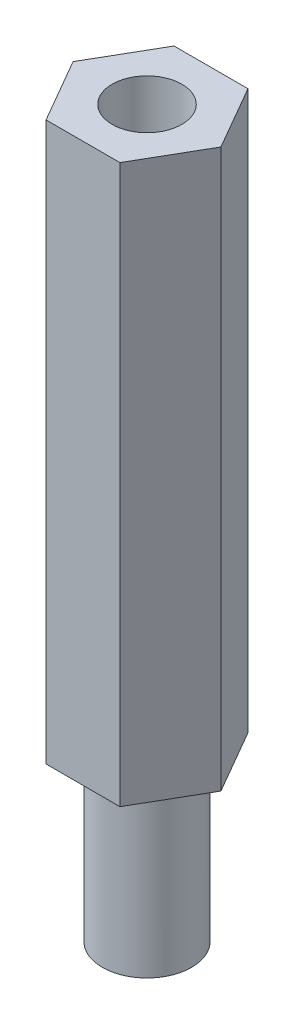
SolidWorks part; units mm, degrees
ref_plane "前视基准面" through (0, 0, 0) normal (0, 0, 1) x (1, 0, 0)
ref_plane "上视基准面" through (0, 0, 0) normal (0, 1, 0) x (1, 0, 0)
ref_plane "右视基准面" through (0, 0, 0) normal (1, 0, 0) x (0, 0, -1)
sketch "草图4" plane through (0, 0, 0) normal (0, 1, 0) x (1, 0, 0)
  line L0 (-12.7945, 0) -> (16.3015, 0) construction
  line L2 (1.325, -2.295) -> (2.65, 0)
  line L3 (2.65, 0) -> (1.325, 2.295)
  line L4 (1.325, 2.295) -> (-1.325, 2.295)
  line L5 (-1.325, 2.295) -> (-2.65, 0)
  line L6 (-2.65, 0) -> (-1.325, -2.295)
  line L7 (-1.325, -2.295) -> (1.325, -2.295)
  circle A0 centre (0, 0) radius 2.295 construction
  dimension "D1" = 5.3
extrude "凸台-拉伸1" add sketch "草图4" along normal blind 20
sketch "草图6" plane through (0, 0, 0) normal (0, -1, 0) x (-1, 0, 0)
  circle A0 centre (0, 0) radius 1.6
  dimension "D1" = 3.2
extrude "凸台-拉伸2" add sketch "草图6" along normal blind 6
cosmetic thread "装饰螺纹线1" parameters "D2"=2.5
sketch "草图7" plane through (0, 20, 0) normal (0, 1, 0) x (1, 0, 0)
  circle A0 centre (0, 0) radius 1.25
  dimension "D1" = 2.5
extrude "切除-拉伸1" cut sketch "草图7" against normal blind 5
cosmetic thread "装饰螺纹线2" parameters "D2"=3
